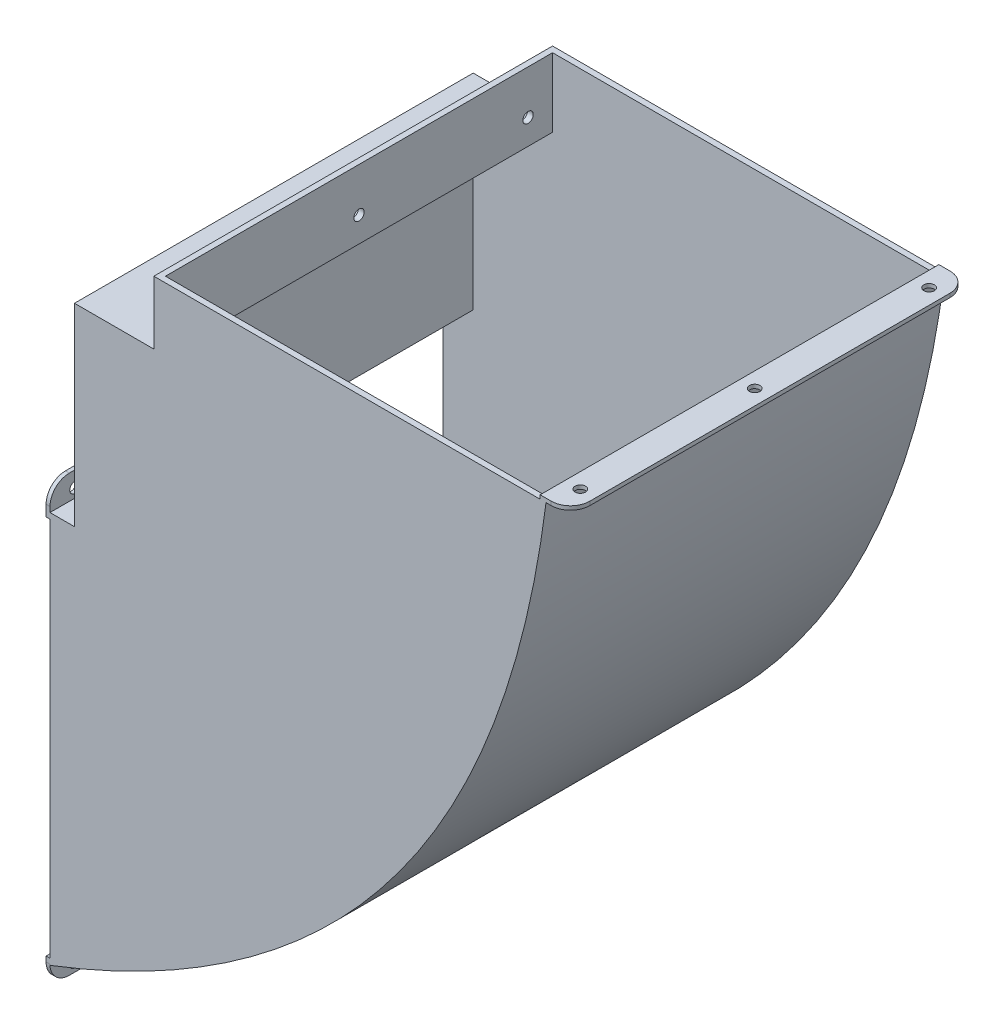
SolidWorks part; units mm, degrees
ref_plane "Front Plane" through (0, 0, 0) normal (0, 0, 1) x (1, 0, 0)
ref_plane "Top Plane" through (0, 0, 0) normal (0, 1, 0) x (1, 0, 0)
ref_plane "Right Plane" through (0, 0, 0) normal (1, 0, 0) x (0, 0, -1)
sketch "Sketch1" plane through (0, 0, 0) normal (0, 0, 1) x (1, 0, 0)
  line L0 (41.1191, -101.5271) -> (244.3191, 101.6729) construction
  line L1 (-12.7, 101.6729) -> (244.3191, 101.6729) construction
  line L2 (-12.7, 101.6729) -> (-12.7, -101.5271) construction
  line L3 (-12.7, -101.5271) -> (244.3191, -101.5271) construction
  line L4 (244.3191, 101.6729) -> (244.3191, -101.5271) construction
  line L5 (-12.7, 101.6729) -> (244.3191, -101.5271) construction
  line L6 (-12.7, -101.5271) -> (244.3191, 101.6729) construction
  line L7 (244.3191, 234.6348) -> (41.1191, 234.6348) construction
  line L8 (244.3191, 234.6348) -> (244.3191, -101.5271) construction
  line L9 (244.3191, -101.5271) -> (41.1191, -101.5271) construction
  line L10 (41.1191, 234.6348) -> (41.1191, -101.5271) construction
  line L11 (244.3191, 234.6348) -> (41.1191, -101.5271) construction
  line L12 (244.3191, -101.5271) -> (41.1191, 234.6348) construction
  line L13 (244.3191, 234.6348) -> (41.1191, 234.6348)
  line L14 (41.1191, 234.6348) -> (41.1191, 201.9348)
  line L15 (41.1191, 201.9348) -> (0, 201.9348)
  line L16 (0, 201.9348) -> (0, 101.6729)
  line L17 (0, 101.6729) -> (-12.7, 101.6729)
  line L18 (33.2, 201.9348) -> (39, 201.9348) construction
  line L19 (0, -111.8652) -> (0, 211.5428) construction
  line L20 (-12.7, 101.6729) -> (-12.7, -101.5271)
  spline S0 degree 2 poles (-12.7, -101.5271) (212.7979, -15.1851) (244.3191, 234.6348) knots 0 0 0 1 1 1
  point P4 (115.8095, 0.0729)
  point P15 (142.7191, 66.5538)
  dimension "D3" = 45
sketch "Sketch3" plane through (0, 0, 0) normal (1, 0, 0) x (0, 0, -1)
  line L0 (0, 101.6729) -> (0, -101.5271) construction
  line L1 (-206.5871, 101.6729) -> (0, 101.6729) construction
  line L2 (-206.5871, 101.6729) -> (-206.5871, -104.9142) construction
  line L3 (-206.5871, -104.9142) -> (0, -104.9142) construction
  line L4 (0, 101.6729) -> (0, -104.9142) construction
  line L5 (-206.5871, 101.6729) -> (0, -104.9142) construction
  line L6 (-206.5871, -104.9142) -> (0, 101.6729) construction
  line L7 (0, 101.6729) -> (0, -101.5271) construction
  point P4 (-103.2935, -1.6207)
extrude "Boss-Extrude3" add sketch "Sketch1" along normal up to vertex (206.5871 mm away) up to point (0, 101.6729, 206.5871)
shell "Shell1" thickness 3
sketch "Sketch4" plane through (0, 234.6348, 0) normal (0, 1, 0) x (1, 0, 0)
  line L2 (257.0191, -10) -> (257.0191, -196.5871)
  line L3 (247.0191, -206.5871) -> (244.3191, -206.5871)
  line L4 (244.3191, -206.5871) -> (41.1191, -206.5871) construction
  line L9 (244.3191, -206.5871) -> (244.3191, 0) construction
  line L12 (241.2952, 0) -> (241.2952, -206.5871)
  line L13 (241.2952, -206.5871) -> (244.3191, -206.5871)
  line L14 (241.2952, 0) -> (247.0191, 0)
  line L15 (244.3191, 0) -> (41.1191, 0) construction
  arc A0 (257.0191, -196.5871) -> (247.0191, -206.5871) centre (247.0191, -196.5871) cw
  arc A3 (247.0191, 0) -> (257.0191, -10) centre (247.0191, -10) cw
  dimension "D3" = 10
  dimension "D1" = 10
  dimension "D2" = 12.7
extrude "Boss-Extrude4" add sketch "Sketch4" along normal blind 2
sketch "Sketch5" plane through (-12.7, 0, 0) normal (-1, 0, 0) x (0, 0, 1)
  line L2 (10, 114.3729) -> (196.5871, 114.3729)
  line L4 (206.5871, 101.6729) -> (0, 101.6729) construction
  line L5 (203.5871, -98.3134) -> (3, -98.3134) construction
  line L9 (206.5871, 104.3729) -> (206.5871, 98.6729)
  line L12 (206.5871, 98.6729) -> (0, 98.6729)
  line L14 (0, 98.6729) -> (0, 104.3729)
  line L17 (0, -98.3134) -> (0, -101.0134)
  line L18 (10, -111.0134) -> (196.5871, -111.0134)
  line L19 (206.5871, -101.0134) -> (206.5871, -98.3134)
  line L20 (206.5871, -98.3134) -> (0, -98.3134)
  line L21 (0, 101.6729) -> (0, -101.5271) construction
  line L23 (206.5871, 101.6729) -> (206.5871, -101.5271) construction
  arc A3 (10, 114.3729) -> (0, 104.3729) centre (10, 104.3729) ccw
  arc A4 (196.5871, 114.3729) -> (206.5871, 104.3729) centre (196.5871, 104.3729) cw
  arc A5 (196.5871, -111.0134) -> (206.5871, -101.0134) centre (196.5871, -101.0134) ccw
  arc A6 (0, -101.0134) -> (10, -111.0134) centre (10, -101.0134) ccw
  point P2 (0, 0)
  point P7 (0, 0)
  dimension "D3" = 12.7
  dimension "D2" = 10
  dimension "D4" = 10
  dimension "D1" = 12.7
extrude "Boss-Extrude5" add sketch "Sketch5" along normal blind 2
sketch "Sketch8" plane through (44.1191, 0, 0) normal (1, 0, 0) x (0, 0, -1)
  line L0 (-103.2935, 214.4348) -> (-103.2935, 209.4348) construction
  line L1 (-203.5871, 234.6348) -> (-3, 234.6348) construction
  line L2 (-203.5871, 234.6348) -> (-203.5871, 198.9348) construction
  line L3 (-203.5871, 198.9348) -> (-3, 198.9348) construction
  line L4 (-3, 234.6348) -> (-3, 198.9348) construction
  line L5 (-203.5871, 234.6348) -> (-3, 198.9348) construction
  line L6 (-203.5871, 198.9348) -> (-3, 234.6348) construction
  line L7 (422.1129, 214.4348) -> (-339.8871, 214.4348) construction
  line L8 (-339.8871, 209.4348) -> (422.1129, 209.4348) construction
  line L9 (-203.5871, 211.9348) -> (-3, 211.9348) construction
  line L12 (-203.5871, 211.9348) -> (-190.8871, 211.9348) construction
  line L13 (-190.8871, 211.9348) -> (-103.2935, 211.9348) construction
  line L14 (-103.2935, 211.9348) -> (-15.7, 211.9348) construction
  line L15 (-15.7, 211.9348) -> (-3, 211.9348) construction
  circle A0 centre (-190.8871, 211.9348) radius 2.7
  circle A1 centre (-103.2935, 211.9348) radius 2.7
  circle A2 centre (-15.7, 211.9348) radius 2.7
  point P4 (-103.2935, 216.7848)
  point P16 (-103.2935, 211.9348)
  point P17 (-103.2935, 211.9348)
  dimension "D1" = 5.4
  dimension "D2" = 12.7
extrude "Cut-Extrude2" cut sketch "Sketch8" against normal up to surface (3 mm away) up to face at (41.1191, 218.2848, 103.2935)
sketch "Sketch9" plane through (0, 236.6348, 0) normal (0, 1, 0) x (1, 0, 0)
  line L0 (257.0191, -103.2935) -> (241.2952, -103.2935) construction
  line L1 (257.0191, -196.5871) -> (257.0191, -10) construction
  line L2 (241.2952, 0) -> (241.2952, -206.5871) construction
  line L3 (249.1571, -0.2312) -> (249.1571, -206.3559) construction
  line L4 (249.1571, -0.2312) -> (249.1571, -12.9312) construction
  line L5 (249.1571, -193.6559) -> (249.1571, -206.3559) construction
  arc A0 (257.0191, -10) -> (247.0191, 0) centre (247.0191, -10) ccw construction
  circle A1 centre (249.1571, -12.9312) radius 2.7
  circle A2 centre (249.1571, -103.2935) radius 2.7
  circle A3 centre (249.1571, -193.6559) radius 2.7
  point P8 (249.1571, -103.2935)
  point P9 (249.1571, -103.2935)
  dimension "D1" = 5.4
  dimension "D2" = 12.7
extrude "Cut-Extrude3" cut sketch "Sketch9" against normal up to surface (2 mm away) up to face at (250.1428, 234.6348, 103.2935)
sketch "Sketch11" plane through (-14.7, 0, 0) normal (-1, 0, 0) x (0, 0, 1)
  line L0 (103.2935, 114.3729) -> (103.2935, 98.6729) construction
  line L1 (196.5871, 114.3729) -> (10, 114.3729) construction
  line L2 (0, 98.6729) -> (206.5871, 98.6729) construction
  line L3 (0.2339, 106.5229) -> (206.3532, 106.5229) construction
  line L6 (193.6532, 106.5229) -> (206.3532, 106.5229) construction
  line L7 (12.9339, 106.5229) -> (0.2339, 106.5229) construction
  line L9 (0, 0) -> (206.5871, 0.0729) construction
  line L10 (206.5871, -101.5271) -> (206.5871, 101.6729) construction
  arc A2 (10, 114.3729) -> (0, 104.3729) centre (10, 104.3729) ccw construction
  circle A3 centre (12.9339, 106.5229) radius 2.7
  circle A4 centre (103.2935, 106.5229) radius 2.7
  circle A5 centre (193.6532, 106.5229) radius 2.7
  circle A6 centre (193.7283, -106.3862) radius 2.7
  circle A7 centre (103.3687, -106.45) radius 2.7
  circle A8 centre (13.009, -106.5137) radius 2.7
  point P14 (103.2935, 106.5229)
  point P15 (103.2935, 106.5229)
  dimension "D1" = 5.4
  dimension "D2" = 12.7
extrude "Cut-Extrude4" cut sketch "Sketch11" against normal up to surface (2 mm away) up to face at (-12.7, 107.4965, 103.2935)
